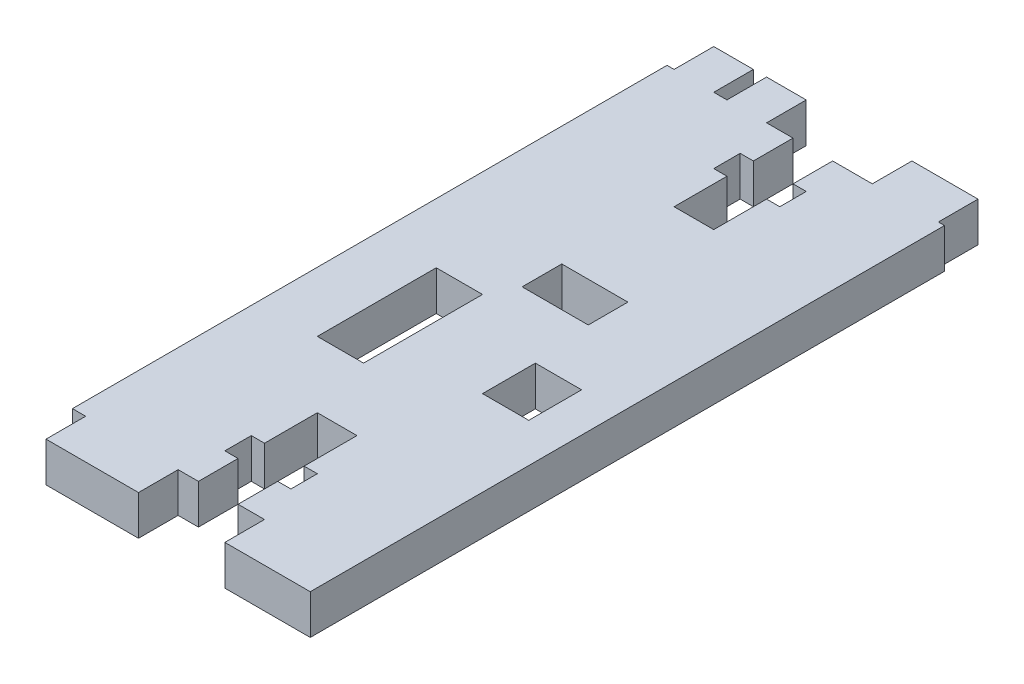
SolidWorks part; units mm, degrees
ref_plane "Alzado" through (0, 0, 0) normal (0, 0, 1) x (1, 0, 0)
ref_plane "Planta" through (0, 0, 0) normal (0, 1, 0) x (1, 0, 0)
ref_plane "Vista lateral" through (0, 0, 0) normal (1, 0, 0) x (0, 0, -1)
sketch "Croquis1" plane through (0, 0, 0) normal (0, 0, 1) x (1, 0, 0)
  line L0 (-323.2345, 58307.5052) -> (-323.2345, 58304.5052)
  line L1 (-326.6991, 58290.5052) -> (-323.1991, 58290.5052)
  line L2 (-326.6991, 58290.5052) -> (-326.6991, 58281.5052)
  line L3 (-326.6991, 58281.5052) -> (-323.1991, 58281.5052)
  line L4 (-323.1991, 58290.5052) -> (-323.1991, 58281.5052)
  line L9 (-316.6991, 58284.0052) -> (-313.1991, 58284.0052)
  line L10 (-316.6991, 58284.0052) -> (-316.6991, 58288.0052)
  line L11 (-316.6991, 58288.0052) -> (-313.1991, 58288.0052)
  line L12 (-313.1991, 58284.0052) -> (-313.1991, 58288.0052)
  line L13 (-323.2345, 58304.5052) -> (-321.6991, 58304.5052)
  line L14 (-321.6991, 58304.5052) -> (-321.6991, 58301.5052)
  line L15 (-321.6991, 58301.5052) -> (-322.6991, 58301.5052)
  line L16 (-322.6991, 58301.5052) -> (-322.6991, 58299.5052)
  line L17 (-322.6991, 58299.5052) -> (-321.6991, 58299.5052)
  line L18 (-321.6991, 58299.5052) -> (-321.6991, 58295.5052)
  line L19 (-321.6991, 58295.5052) -> (-318.6991, 58295.5052)
  line L20 (-318.6991, 58295.5052) -> (-318.6991, 58299.5052)
  line L21 (-318.6991, 58299.5052) -> (-317.6991, 58299.5052)
  line L22 (-317.6991, 58299.5052) -> (-317.6991, 58301.5052)
  line L23 (-317.6991, 58301.5052) -> (-318.6991, 58301.5052)
  line L24 (-318.6991, 58301.5052) -> (-318.6991, 58304.5052)
  line L25 (-318.6991, 58304.5052) -> (-316.6991, 58304.5052)
  line L26 (-316.6991, 58304.5052) -> (-316.6991, 58307.5052)
  line L27 (-316.6991, 58307.5052) -> (-310.2345, 58307.5052)
  line L28 (-310.2345, 58307.5052) -> (-310.2345, 58259.5052)
  line L29 (-310.2345, 58259.5052) -> (-310.6991, 58259.5052)
  line L30 (-310.6991, 58259.5052) -> (-310.6991, 58256.5052)
  line L31 (-310.6991, 58256.5052) -> (-315.6991, 58256.5052)
  line L32 (-315.6991, 58256.5052) -> (-315.6991, 58259.5052)
  line L33 (-315.6991, 58259.5052) -> (-318.6991, 58259.5052)
  line L34 (-318.6991, 58259.5052) -> (-318.6991, 58262.5052)
  line L35 (-318.6991, 58262.5052) -> (-317.6991, 58262.5052)
  line L36 (-317.6991, 58262.5052) -> (-317.6991, 58264.5052)
  line L37 (-317.6991, 58264.5052) -> (-318.6991, 58264.5052)
  line L38 (-318.6991, 58264.5052) -> (-318.6991, 58268.5052)
  line L39 (-318.6991, 58268.5052) -> (-321.6991, 58268.5052)
  line L40 (-321.6991, 58268.5052) -> (-321.6991, 58264.5052)
  line L41 (-321.6991, 58264.5052) -> (-322.6991, 58264.5052)
  line L42 (-322.6991, 58264.5052) -> (-322.6991, 58262.5052)
  line L43 (-322.6991, 58262.5052) -> (-321.6991, 58262.5052)
  line L44 (-321.6991, 58262.5052) -> (-321.6991, 58259.5052)
  line L45 (-321.6991, 58259.5052) -> (-323.6991, 58259.5052)
  line L46 (-323.6991, 58259.5052) -> (-323.6991, 58256.5052)
  line L47 (-323.6991, 58256.5052) -> (-326.6991, 58256.5052)
  line L48 (-326.6991, 58256.5052) -> (-326.6991, 58259.5052)
  line L49 (-326.6991, 58259.5052) -> (-327.6991, 58259.5052)
  line L50 (-327.6991, 58259.5052) -> (-327.6991, 58256.5052)
  line L51 (-327.6991, 58256.5052) -> (-330.6991, 58256.5052)
  line L52 (-330.6991, 58256.5052) -> (-330.6991, 58259.5052)
  line L53 (-330.6991, 58259.5052) -> (-331.2345, 58259.5052)
  line L54 (-331.2345, 58259.5052) -> (-331.2345, 58304.5052)
  line L55 (-331.2345, 58304.5052) -> (-330.2345, 58304.5052)
  line L56 (-330.2345, 58304.5052) -> (-330.2345, 58307.5052)
  line L57 (-330.2345, 58307.5052) -> (-323.2345, 58307.5052)
  line L59 (-317.1956, 58276.5052) -> (-317.1956, 58279.5052)
  line L63 (-322.1991, 58279.5052) -> (-317.1956, 58279.5052)
  line L64 (-322.1991, 58279.5052) -> (-322.1991, 58276.5052)
  line L65 (-322.1991, 58276.5052) -> (-317.1956, 58276.5052)
extrude "Saliente-Extruir1" add sketch "Croquis1" along normal blind 3
move or copy body "Sólido-Mover/Copiar1" bodies to move or copy 101 copy no rotation origin (0, 58282.0052, 1.5) rotation axis (1, 0, 0) rotation angle 90
